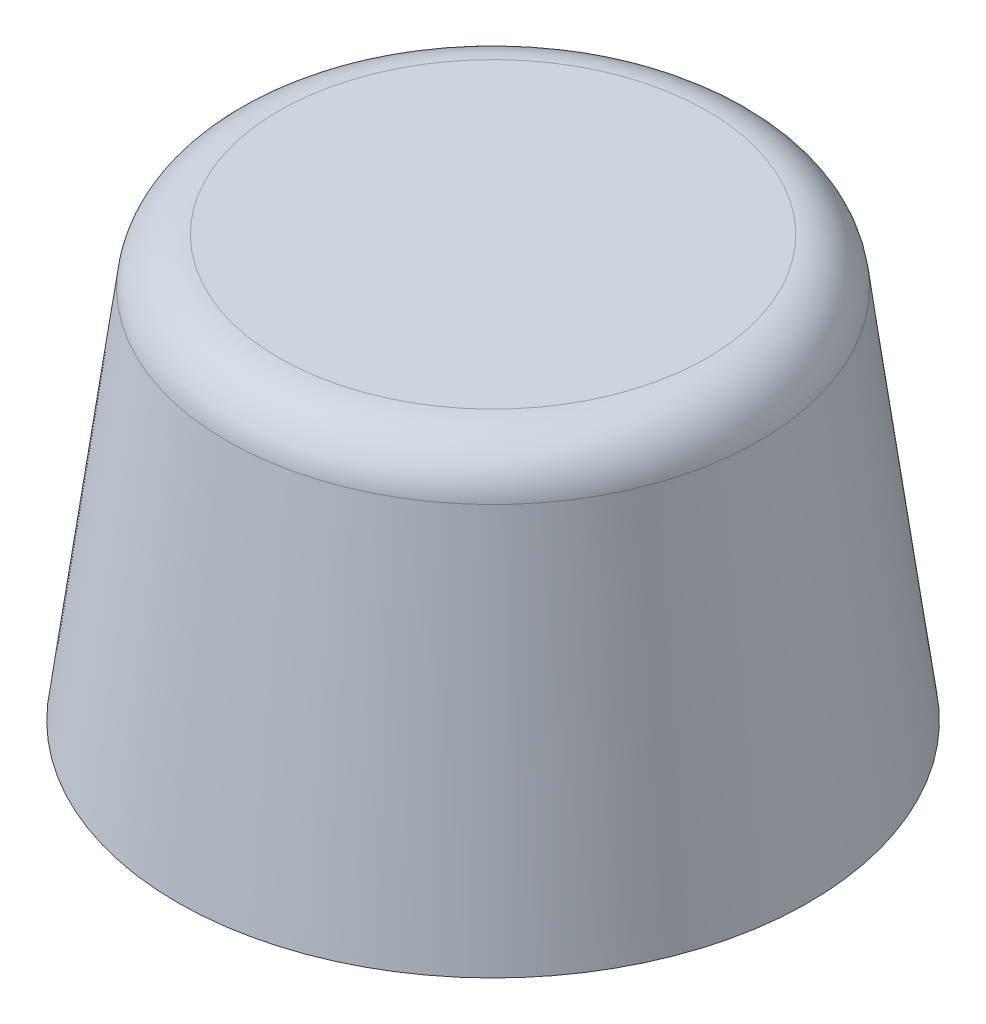
SolidWorks part; units mm, degrees
ref_plane "Front Plane" through (0, 0, 0) normal (0, 0, 1) x (1, 0, 0)
ref_plane "Top Plane" through (0, 0, 0) normal (0, 1, 0) x (1, 0, 0)
ref_plane "Right Plane" through (0, 0, 0) normal (1, 0, 0) x (0, 0, -1)
sketch "Sketch1" plane through (0, 0, 0) normal (0, 1, 0) x (1, 0, 0)
  circle A0 centre (0, 0) radius 9.525
  dimension "D1" = 19.05
extrude "Boss-Extrude1" add sketch "Sketch1" along normal blind 12.7 draft 7.5
sketch "Sketch2" plane through (0, 0, 0) normal (0, -1, 0) x (1, 0, 0)
  line L0 (-3.175, 3.175) -> (3.175, 3.175) construction
  line L1 (-2.8511, -1.397) -> (2.8511, -1.397)
  arc A0 (2.8511, -1.397) -> (-2.8511, -1.397) centre (0, 0) ccw
  point P6 (0, 3.175)
  dimension "D1" = 6.35
  dimension "D2" = 6.35
  dimension "D3" = 4.572
extrude "Cut-Extrude1" cut sketch "Sketch2" against normal blind 9.525
sketch "Sketch3" plane through (0, 0, 0) normal (0, -1, 0) x (1, 0, 0)
  circle A0 centre (0, 0) radius 3.175
  arc A1 (2.8511, -1.397) -> (-2.8511, -1.397) centre (0, 0) ccw construction
extrude "Cut-Extrude2" cut sketch "Sketch3" against normal blind 2.54
fillet "Fillet3" radius 1.5875 1 edges at (0, 12.7, 7.853)
